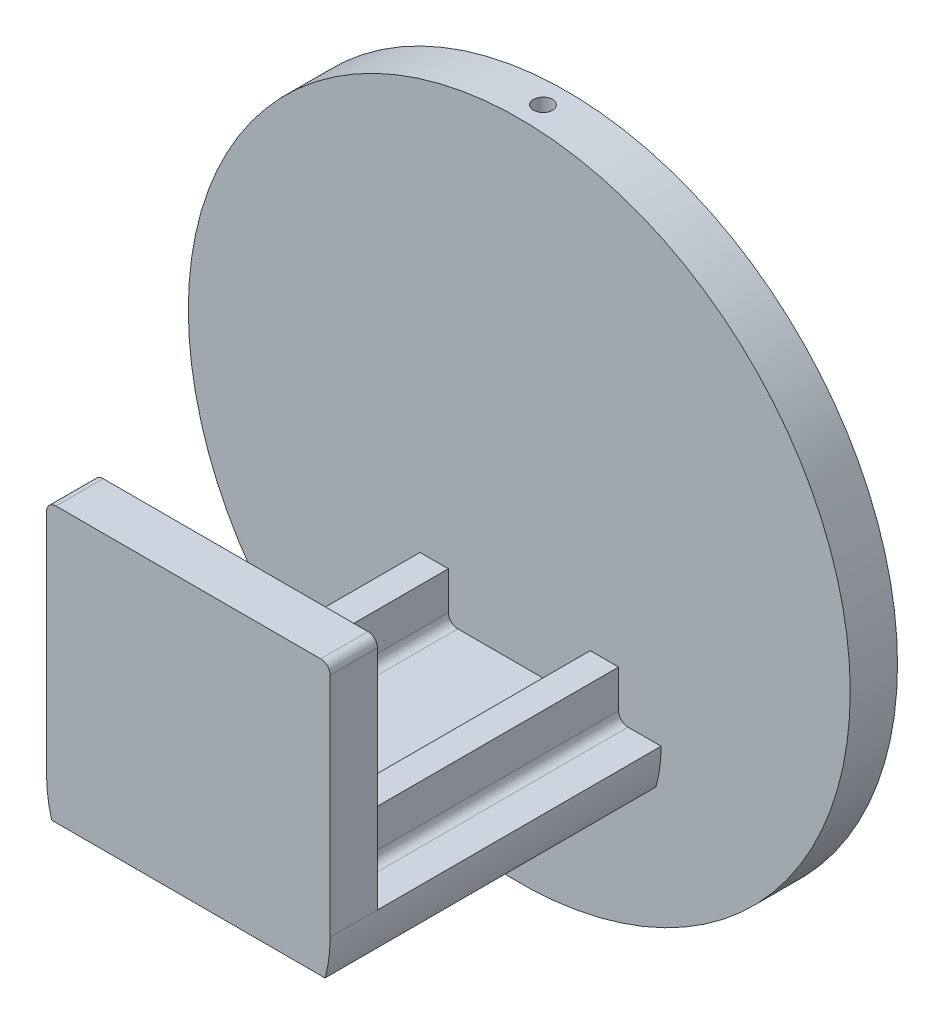
SolidWorks part; units mm, degrees
material "ABS"
ref_plane "Front Plane" through (0, 0, 0) normal (0, 0, 1) x (1, 0, 0)
ref_plane "Top Plane" through (0, 0, 0) normal (0, 1, 0) x (1, 0, 0)
ref_plane "Right Plane" through (0, 0, 0) normal (1, 0, 0) x (0, 0, -1)
sketch "Sketch1" plane through (0, 0, 0) normal (0, 0, 1) x (1, 0, 0)
  line L0 (-19.1629, -8.3607) -> (19.1629, -8.3607)
  line L1 (0, -8.3607) -> (0, -12.5855) construction
  line L2 (-18.6913, -12.5855) -> (18.6913, -12.5855)
  circle A0 centre (0, 0) radius 35
  arc A1 (18.6913, -12.5855) -> (19.1629, -8.3607) centre (0, -8.3607) ccw
  arc A2 (-18.6913, -12.5855) -> (-19.1629, -8.3607) centre (0, -8.3607) cw
  point P5 (0, -8.3607)
  point P9 (0, -12.5855)
  dimension "D1" = 70
extrude "Boss-Extrude1" add sketch "Sketch1" against normal blind 5 contours A0
sketch "Sketch2" plane through (0, 0, 0) normal (0, 0, 1) x (1, 0, 0)
  line L0 (-15, -15) -> (15, -15)
  line L1 (0, 0) -> (0, -26.4743) construction
  line L2 (-14.4568, -19) -> (14.4568, -19)
  arc A0 (14.4568, -19) -> (15, -15) centre (0, -15) ccw
  arc A1 (-14.4568, -19) -> (-15, -15) centre (0, -15) cw
  point P5 (0, -15)
  point P8 (0, -19)
  dimension "D2" = 15
  dimension "D1" = 4
  dimension "D3" = 28.9137
  dimension "D4" = 30
  dimension "D5" = 15
extrude "Boss-Extrude2" add sketch "Sketch2" along normal blind 35
sketch "Sketch3" plane through (0, -15, 0) normal (0, 1, 0) x (1, 0, 0)
  line L0 (15, -30) -> (-15, -30)
  line L1 (15, -35) -> (15, 0) construction
  line L2 (-15, -35) -> (-15, 0) construction
  line L3 (-15, -30) -> (-15, -35)
  line L4 (-15, -35) -> (15, -35)
  line L5 (15, -35) -> (-15, -35) construction
  line L6 (15, -35) -> (15, -30)
  dimension "D1" = 5
extrude "Boss-Extrude3" add sketch "Sketch3" along normal blind 25
sketch "Sketch4" plane through (0, -15, 0) normal (0, 1, 0) x (1, 0, 0)
  line L0 (0, 0) -> (0, -35) construction
  line L1 (-15, -35) -> (15, -35) construction
  line L2 (7.5, 0) -> (7.5, -30)
  line L3 (15, 0) -> (-15, 0) construction
  line L4 (15, -30) -> (-15, -30) construction
  line L5 (7.5, -30) -> (10.5, -30)
  line L6 (10.5, -30) -> (10.5, 0)
  line L7 (10.5, 0) -> (7.5, 0)
  line L8 (-7.5, -30) -> (-10.5, -30)
  line L9 (-10.5, -30) -> (-10.5, 0)
  line L10 (-7.5, 0) -> (-7.5, -30)
  line L11 (-10.5, 0) -> (-7.5, 0)
  dimension "D1" = 7.5
  dimension "D2" = 3
extrude "Boss-Extrude5" add sketch "Sketch4" along normal blind 5
sketch "Sketch5" plane through (0, 0, 0) normal (0, 1, 0) x (1, 0, 0)
  line L0 (7.5, 0) -> (-7.5, 0) construction
  circle A0 centre (0, 2.5) radius 1
  dimension "D2" = 2
  dimension "D1" = 2.5
extrude "Cut-Extrude1" cut sketch "Sketch5" against normal through all and the other way blind 38 contours A0
fillet "Fillet1" radius 1 2 edges at (15, 10, 32.5) (-15, 10, 32.5)
fillet "Fillet2" radius 1 2 edges at (-7.5, -15, 15) (7.5, -15, 15)
fillet "Fillet3" radius 1 2 edges at (10.5, -15, 15) (-10.5, -15, 15)
sketch "Sketch6" plane through (0, 0, -5) normal (0, 0, -1) x (-1, 0, 0)
  line L0 (0, 35) -> (0, -35) construction
  line L1 (-35, 0) -> (35, 0) construction
  circle A0 centre (0, 0) radius 35 construction
  circle A1 centre (0, 11) radius 0.5
  circle A2 centre (0, -11) radius 0.5
  dimension "D1" = 1
  dimension "D2" = 11
extrude "Cut-Extrude2" cut sketch "Sketch6" against normal up to next
